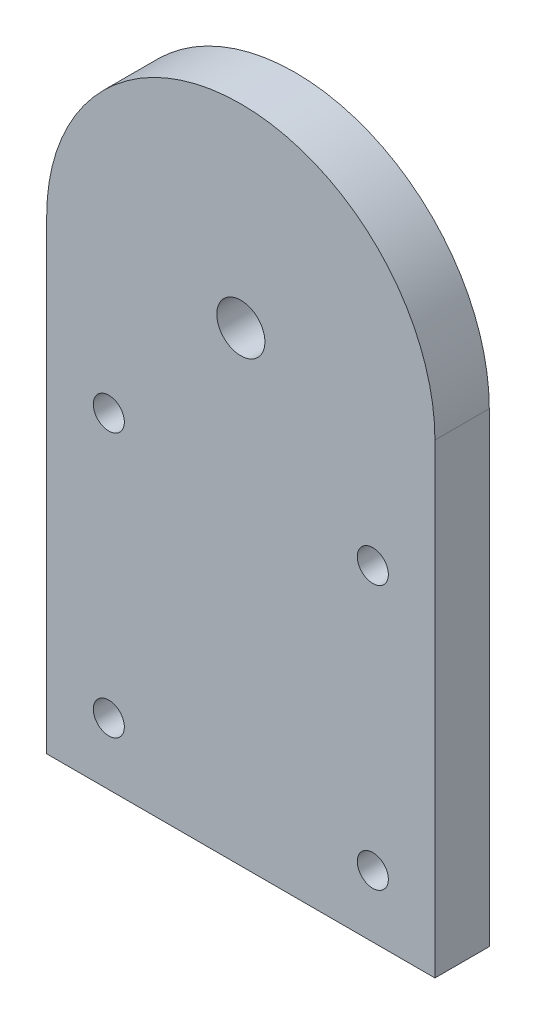
SolidWorks part; units mm, degrees
ref_plane "Ebene vorne" through (0, 0, 0) normal (0, 0, 1) x (1, 0, 0)
ref_plane "Ebene oben" through (0, 0, 0) normal (0, 1, 0) x (1, 0, 0)
ref_plane "Ebene rechts" through (0, 0, 0) normal (1, 0, 0) x (0, 0, -1)
sketch "Skizze1" plane through (0, 0, 0) normal (0, 0, 1) x (1, 0, 0)
  line L0 (0, 72.6505) -> (0, -81.8124) construction
  line L2 (-25, 0) -> (-25, -60)
  line L3 (-25, -60) -> (25, -60)
  line L4 (25, 0) -> (25, -60)
  line L5 (-75.1032, -35) -> (75.5576, -35) construction
  arc A0 (25, 0) -> (-25, 0) centre (0, 0) ccw
  circle A1 centre (0, 0) radius 3.1
  circle A2 centre (-17, -18) radius 2
  circle A3 centre (-17, -52) radius 2
  circle A4 centre (17, -18) radius 2
  circle A5 centre (17, -52) radius 2
  dimension "D1" = 50
  dimension "D3" = 6.2
  dimension "D5" = 4
  dimension "D2" = 60
  dimension "D4" = 25
  dimension "D6" = 34
  dimension "D7" = 34
extrude "Aufsatz-Linear austragen1" add sketch "Skizze1" along normal blind 7
sketch "Skizze2" plane through (0, 0, 0) normal (0, 0, -1) x (-1, 0, 0)
  circle A0 centre (0, 0) radius 3.1 construction
  circle A1 centre (0, 0) radius 3.1
  circle A2 centre (0, 0) radius 5.95
  dimension "D1" = 11.9
extrude "Aufsatz-Linear austragen2" add sketch "Skizze2" along normal blind 7
sketch "Skizze3" plane through (0, 0, 0) normal (0, 0, -1) x (-1, 0, 0)
  circle A0 centre (0, 0) radius 5.95 construction
  circle A1 centre (0, 0) radius 5.95
  circle A2 centre (0, 0) radius 11
  dimension "D1" = 22
extrude "Aufsatz-Linear austragen3" add sketch "Skizze3" along normal blind 5
